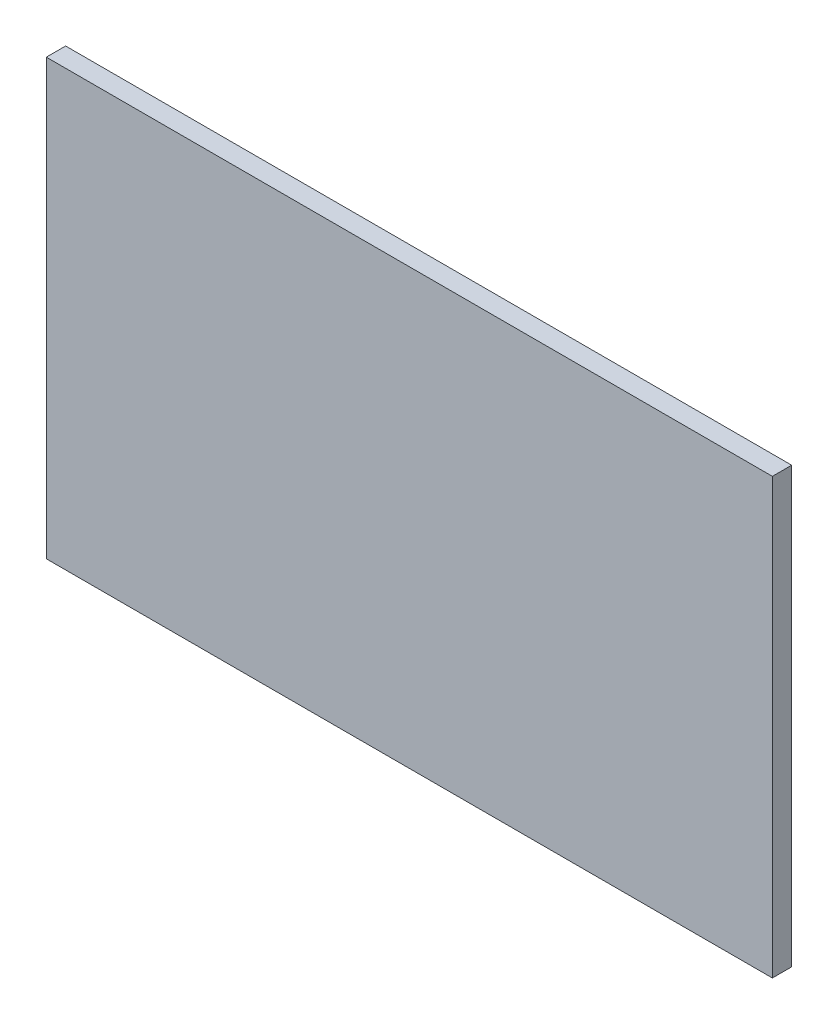
SolidWorks part; units mm, degrees
ref_plane "Спереди" through (0, 0, 0) normal (0, 0, 1) x (1, 0, 0)
ref_plane "Сверху" through (0, 0, 0) normal (0, 1, 0) x (1, 0, 0)
ref_plane "Справа" through (0, 0, 0) normal (1, 0, 0) x (0, 0, -1)
sketch "Эскиз1" plane through (0, 0, 0) normal (0, 0, 1) x (1, 0, 0)
  line L0 (0, 44.5194) -> (0, -185.4806) construction
  line L22 (-18, 39.5194) -> (-18, -185.4806) construction
  line L57 (188, 36.5194) -> (-188, 36.5194) construction
  line L85 (-53, 39.5194) -> (-53, -185.4806) construction
  line L122 (-188, -185.4806) -> (188, -185.4806)
  line L274 (-188, 39.5194) -> (-188, -185.4806)
  line L287 (-120.5, -2.6306) -> (-143, -2.6306)
  line L295 (-143, -2.6306) -> (-143, -11.8306)
  line L331 (188, -182.4806) -> (-188, -182.4806) construction
  line L332 (-185, -185.4806) -> (-185, 39.5194) construction
  line L345 (18, 39.5194) -> (18, -185.4806) construction
  line L348 (188, 39.5194) -> (188, -185.4806)
  line L349 (185, -185.4806) -> (185, 39.5194) construction
  line L361 (53, 39.5194) -> (53, -185.4806) construction
  line L619 (188, 39.5194) -> (-188, 39.5194)
  line L621 (-57.4, -29.0806) -> (-57.4, -17.8806)
  line L622 (-57.4, -17.8806) -> (-68.6, -17.8806)
  line L623 (-68.6, -29.0806) -> (-68.6, -17.8806)
  line L624 (-57.4, -29.0806) -> (-68.6, -29.0806)
  line L626 (-98, -2.6306) -> (-98, -11.8306)
  line L628 (-120.5, -11.8306) -> (-143, -11.8306)
  line L629 (-164.4, -29.0806) -> (-164.4, -17.8806)
  line L630 (-164.4, -17.8806) -> (-175.6, -17.8806)
  line L631 (-175.6, -29.0806) -> (-175.6, -17.8806)
  line L632 (-164.4, -29.0806) -> (-175.6, -29.0806)
  line L633 (-164.4, 0.9194) -> (-175.6, 0.9194)
  line L634 (-175.6, 0.9194) -> (-175.6, 12.1194)
  line L635 (-164.4, 12.1194) -> (-175.6, 12.1194)
  line L636 (-164.4, 0.9194) -> (-164.4, 12.1194)
  line L637 (-135.4, 0.9194) -> (-146.6, 0.9194)
  line L638 (-146.6, 0.9194) -> (-146.6, 12.1194)
  line L639 (-135.4, 12.1194) -> (-146.6, 12.1194)
  line L640 (-135.4, 0.9194) -> (-135.4, 12.1194)
  line L641 (-106.4, 0.9194) -> (-117.6, 0.9194)
  line L642 (-117.6, 0.9194) -> (-117.6, 12.1194)
  line L643 (-106.4, 12.1194) -> (-117.6, 12.1194)
  line L644 (-106.4, 0.9194) -> (-106.4, 12.1194)
  line L646 (-143, -2.6306) -> (-143, -11.8306)
  line L648 (-98, -11.8306) -> (-120.5, -11.8306)
  line L649 (-77.4, 0.9194) -> (-88.6, 0.9194)
  line L650 (-88.6, 0.9194) -> (-88.6, 12.1194)
  line L651 (-77.4, 12.1194) -> (-88.6, 12.1194)
  line L652 (-77.4, 0.9194) -> (-77.4, 12.1194)
  line L653 (-57.4, 0.9194) -> (-68.6, 0.9194)
  line L654 (-68.6, 0.9194) -> (-68.6, 12.1194)
  line L655 (-57.4, 12.1194) -> (-68.6, 12.1194)
  line L656 (-57.4, 0.9194) -> (-57.4, 12.1194)
  line L657 (-57.4, 18.9194) -> (-68.6, 18.9194)
  line L658 (-68.6, 18.9194) -> (-68.6, 30.1194)
  line L659 (-57.4, 30.1194) -> (-68.6, 30.1194)
  line L660 (-57.4, 18.9194) -> (-57.4, 30.1194)
  line L661 (-59.4, -96.8806) -> (-59.4, -110.0806)
  line L662 (-73.6, -110.0806) -> (-59.4, -110.0806)
  line L663 (-73.6, -96.8806) -> (-73.6, -110.0806)
  line L664 (-73.6, -96.8806) -> (-59.4, -96.8806)
  line L665 (-43.6, -121.0806) -> (-43.6, -109.8806)
  line L666 (-32.4, -109.8806) -> (-43.6, -109.8806)
  line L667 (-32.4, -121.0806) -> (-32.4, -109.8806)
  line L668 (-32.4, -121.0806) -> (-43.6, -121.0806)
  line L669 (-85.9, -115.8806) -> (-97.1, -115.8806)
  line L670 (-97.1, -127.0806) -> (-97.1, -115.8806)
  line L671 (-85.9, -127.0806) -> (-97.1, -127.0806)
  line L672 (-85.9, -127.0806) -> (-85.9, -115.8806)
  line L673 (-110.9, -115.8806) -> (-122.1, -115.8806)
  line L674 (-122.1, -127.0806) -> (-122.1, -115.8806)
  line L675 (-110.9, -127.0806) -> (-122.1, -127.0806)
  line L676 (-110.9, -127.0806) -> (-110.9, -115.8806)
  line L677 (-133.4, -131.3806) -> (-149.6, -131.3806)
  line L678 (-149.6, -147.5806) -> (-149.6, -131.3806)
  line L679 (-133.4, -147.5806) -> (-149.6, -147.5806)
  line L680 (-133.4, -147.5806) -> (-133.4, -131.3806)
  line L681 (-108.4, -131.3806) -> (-124.6, -131.3806)
  line L682 (-124.6, -147.5806) -> (-124.6, -131.3806)
  line L683 (-108.4, -147.5806) -> (-124.6, -147.5806)
  line L684 (-108.4, -147.5806) -> (-108.4, -131.3806)
  line L685 (-83.4, -131.3806) -> (-99.6, -131.3806)
  line L686 (-99.6, -147.5806) -> (-99.6, -131.3806)
  line L687 (-83.4, -147.5806) -> (-99.6, -147.5806)
  line L688 (-83.4, -147.5806) -> (-83.4, -131.3806)
  line L689 (-58.4, -131.3806) -> (-74.6, -131.3806)
  line L690 (-74.6, -147.5806) -> (-74.6, -131.3806)
  line L691 (-58.4, -147.5806) -> (-74.6, -147.5806)
  line L692 (-58.4, -147.5806) -> (-58.4, -131.3806)
  line L693 (-60.9, -151.8806) -> (-72.1, -151.8806)
  line L694 (-72.1, -163.0806) -> (-72.1, -151.8806)
  line L695 (-60.9, -163.0806) -> (-72.1, -163.0806)
  line L696 (-60.9, -163.0806) -> (-60.9, -151.8806)
  line L697 (-85.9, -151.8806) -> (-97.1, -151.8806)
  line L698 (-97.1, -163.0806) -> (-97.1, -151.8806)
  line L699 (-85.9, -163.0806) -> (-97.1, -163.0806)
  line L700 (-85.9, -163.0806) -> (-85.9, -151.8806)
  line L701 (-110.9, -151.8806) -> (-122.1, -151.8806)
  line L702 (-122.1, -163.0806) -> (-122.1, -151.8806)
  line L703 (-110.9, -163.0806) -> (-122.1, -163.0806)
  line L704 (-110.9, -163.0806) -> (-110.9, -151.8806)
  line L705 (-135.9, -151.8806) -> (-147.1, -151.8806)
  line L706 (-147.1, -163.0806) -> (-147.1, -151.8806)
  line L707 (-135.9, -163.0806) -> (-147.1, -163.0806)
  line L708 (-135.9, -163.0806) -> (-135.9, -151.8806)
  line L709 (-169.55, -161.5806) -> (-169.55, -135.3806)
  line L710 (-169.55, -135.3806) -> (-170.45, -135.3806)
  line L711 (-170.45, -161.5806) -> (-170.45, -135.3806)
  line L712 (-169.55, -161.5806) -> (-170.45, -161.5806)
  line L713 (-135.9, -181.0806) -> (-147.1, -181.0806)
  line L714 (-147.1, -181.0806) -> (-147.1, -169.8806)
  line L715 (-135.9, -169.8806) -> (-147.1, -169.8806)
  line L716 (-135.9, -181.0806) -> (-135.9, -169.8806)
  line L717 (-110.9, -181.0806) -> (-122.1, -181.0806)
  line L718 (-122.1, -181.0806) -> (-122.1, -169.8806)
  line L719 (-110.9, -169.8806) -> (-122.1, -169.8806)
  line L720 (-110.9, -181.0806) -> (-110.9, -169.8806)
  line L721 (-85.9, -181.0806) -> (-97.1, -181.0806)
  line L722 (-97.1, -181.0806) -> (-97.1, -169.8806)
  line L723 (-85.9, -169.8806) -> (-97.1, -169.8806)
  line L724 (-85.9, -181.0806) -> (-85.9, -169.8806)
  line L725 (-72.1, -181.0806) -> (-72.1, -169.8806)
  line L726 (-60.9, -169.8806) -> (-72.1, -169.8806)
  line L727 (-60.9, -181.0806) -> (-60.9, -169.8806)
  line L728 (-60.9, -181.0806) -> (-72.1, -181.0806)
  line L729 (-37.55, -158.5806) -> (-37.55, -132.3806)
  line L730 (-37.55, -132.3806) -> (-38.45, -132.3806)
  line L731 (-38.45, -158.5806) -> (-38.45, -132.3806)
  line L732 (-37.55, -158.5806) -> (-38.45, -158.5806)
  line L733 (-27.6, -157.7806) -> (-27.6, -133.1806)
  line L734 (-18.4, -133.1806) -> (-27.6, -133.1806)
  line L735 (-18.4, -157.7806) -> (-18.4, -133.1806)
  line L736 (-18.4, -157.7806) -> (-27.6, -157.7806)
  line L737 (13.1, -175.0306) -> (-13.1, -175.0306)
  line L738 (-13.1, -175.0306) -> (-13.1, -175.9306)
  line L739 (13.1, -175.9306) -> (-13.1, -175.9306)
  line L740 (13.1, -175.0306) -> (13.1, -175.9306)
  line L741 (5.6, -121.0806) -> (-5.6, -121.0806)
  line L742 (-5.6, -121.0806) -> (-5.6, -109.8806)
  line L743 (5.6, -109.8806) -> (-5.6, -109.8806)
  line L744 (5.6, -121.0806) -> (5.6, -109.8806)
  line L745 (32.4, -121.0806) -> (43.6, -121.0806)
  line L746 (43.6, -121.0806) -> (43.6, -109.8806)
  line L747 (32.4, -109.8806) -> (43.6, -109.8806)
  line L748 (32.4, -121.0806) -> (32.4, -109.8806)
  line L749 (73.6, -110.0806) -> (59.4, -110.0806)
  line L750 (59.4, -96.8806) -> (59.4, -110.0806)
  line L751 (73.6, -96.8806) -> (59.4, -96.8806)
  line L752 (73.6, -96.8806) -> (73.6, -110.0806)
  line L753 (85.9, -127.0806) -> (85.9, -115.8806)
  line L754 (85.9, -115.8806) -> (97.1, -115.8806)
  line L755 (97.1, -127.0806) -> (97.1, -115.8806)
  line L756 (85.9, -127.0806) -> (97.1, -127.0806)
  line L757 (58.4, -131.3806) -> (74.6, -131.3806)
  line L758 (74.6, -147.5806) -> (74.6, -131.3806)
  line L759 (58.4, -147.5806) -> (74.6, -147.5806)
  line L760 (58.4, -147.5806) -> (58.4, -131.3806)
  line L761 (83.4, -131.3806) -> (99.6, -131.3806)
  line L762 (99.6, -147.5806) -> (99.6, -131.3806)
  line L763 (83.4, -147.5806) -> (99.6, -147.5806)
  line L764 (83.4, -147.5806) -> (83.4, -131.3806)
  line L765 (110.9, -127.0806) -> (110.9, -115.8806)
  line L766 (110.9, -115.8806) -> (122.1, -115.8806)
  line L767 (122.1, -127.0806) -> (122.1, -115.8806)
  line L768 (110.9, -127.0806) -> (122.1, -127.0806)
  line L769 (38.45, -158.5806) -> (38.45, -132.3806)
  line L770 (37.55, -132.3806) -> (38.45, -132.3806)
  line L771 (37.55, -158.5806) -> (37.55, -132.3806)
  line L772 (37.55, -158.5806) -> (38.45, -158.5806)
  line L773 (18.4, -133.1806) -> (27.6, -133.1806)
  line L774 (27.6, -157.7806) -> (27.6, -133.1806)
  line L775 (18.4, -157.7806) -> (27.6, -157.7806)
  line L776 (18.4, -157.7806) -> (18.4, -133.1806)
  line L777 (60.9, -181.0806) -> (60.9, -169.8806)
  line L778 (60.9, -169.8806) -> (72.1, -169.8806)
  line L779 (72.1, -181.0806) -> (72.1, -169.8806)
  line L780 (60.9, -181.0806) -> (72.1, -181.0806)
  line L781 (60.9, -163.0806) -> (60.9, -151.8806)
  line L782 (60.9, -151.8806) -> (72.1, -151.8806)
  line L783 (72.1, -163.0806) -> (72.1, -151.8806)
  line L784 (60.9, -163.0806) -> (72.1, -163.0806)
  line L785 (85.9, -163.0806) -> (85.9, -151.8806)
  line L786 (85.9, -151.8806) -> (97.1, -151.8806)
  line L787 (97.1, -163.0806) -> (97.1, -151.8806)
  line L788 (85.9, -163.0806) -> (97.1, -163.0806)
  line L789 (85.9, -181.0806) -> (85.9, -169.8806)
  line L790 (85.9, -169.8806) -> (97.1, -169.8806)
  line L791 (97.1, -181.0806) -> (97.1, -169.8806)
  line L792 (85.9, -181.0806) -> (97.1, -181.0806)
  line L793 (110.9, -181.0806) -> (110.9, -169.8806)
  line L794 (110.9, -169.8806) -> (122.1, -169.8806)
  line L795 (122.1, -181.0806) -> (122.1, -169.8806)
  line L796 (110.9, -181.0806) -> (122.1, -181.0806)
  line L797 (110.9, -163.0806) -> (110.9, -151.8806)
  line L798 (110.9, -151.8806) -> (122.1, -151.8806)
  line L799 (122.1, -163.0806) -> (122.1, -151.8806)
  line L800 (110.9, -163.0806) -> (122.1, -163.0806)
  line L801 (108.4, -147.5806) -> (108.4, -131.3806)
  line L802 (108.4, -131.3806) -> (124.6, -131.3806)
  line L803 (124.6, -147.5806) -> (124.6, -131.3806)
  line L804 (108.4, -147.5806) -> (124.6, -147.5806)
  line L805 (133.4, -147.5806) -> (133.4, -131.3806)
  line L806 (133.4, -131.3806) -> (149.6, -131.3806)
  line L807 (149.6, -147.5806) -> (149.6, -131.3806)
  line L808 (133.4, -147.5806) -> (149.6, -147.5806)
  line L809 (135.9, -163.0806) -> (135.9, -151.8806)
  line L810 (135.9, -151.8806) -> (147.1, -151.8806)
  line L811 (147.1, -163.0806) -> (147.1, -151.8806)
  line L812 (135.9, -163.0806) -> (147.1, -163.0806)
  line L813 (135.9, -181.0806) -> (135.9, -169.8806)
  line L814 (135.9, -169.8806) -> (147.1, -169.8806)
  line L815 (147.1, -181.0806) -> (147.1, -169.8806)
  line L816 (135.9, -181.0806) -> (147.1, -181.0806)
  line L817 (170.45, -161.5806) -> (170.45, -135.3806)
  line L818 (169.55, -135.3806) -> (170.45, -135.3806)
  line L819 (169.55, -161.5806) -> (169.55, -135.3806)
  line L820 (169.55, -161.5806) -> (170.45, -161.5806)
  line L821 (57.4, -17.8806) -> (68.6, -17.8806)
  line L822 (68.6, -29.0806) -> (68.6, -17.8806)
  line L823 (57.4, -29.0806) -> (68.6, -29.0806)
  line L824 (57.4, -29.0806) -> (57.4, -17.8806)
  line L825 (57.4, 0.9194) -> (68.6, 0.9194)
  line L826 (68.6, 0.9194) -> (68.6, 12.1194)
  line L827 (57.4, 12.1194) -> (68.6, 12.1194)
  line L828 (57.4, 0.9194) -> (57.4, 12.1194)
  line L829 (88.6, 0.9194) -> (77.4, 0.9194)
  line L830 (77.4, 0.9194) -> (77.4, 12.1194)
  line L831 (88.6, 12.1194) -> (77.4, 12.1194)
  line L832 (88.6, 0.9194) -> (88.6, 12.1194)
  line L833 (117.6, 0.9194) -> (106.4, 0.9194)
  line L834 (106.4, 0.9194) -> (106.4, 12.1194)
  line L835 (117.6, 12.1194) -> (106.4, 12.1194)
  line L836 (117.6, 0.9194) -> (117.6, 12.1194)
  line L837 (146.6, 0.9194) -> (135.4, 0.9194)
  line L838 (135.4, 0.9194) -> (135.4, 12.1194)
  line L839 (146.6, 12.1194) -> (135.4, 12.1194)
  line L840 (146.6, 0.9194) -> (146.6, 12.1194)
  line L841 (175.6, 0.9194) -> (164.4, 0.9194)
  line L842 (164.4, 0.9194) -> (164.4, 12.1194)
  line L843 (175.6, 12.1194) -> (164.4, 12.1194)
  line L844 (175.6, 0.9194) -> (175.6, 12.1194)
  line L845 (164.4, -17.8806) -> (175.6, -17.8806)
  line L846 (175.6, -29.0806) -> (175.6, -17.8806)
  line L847 (164.4, -29.0806) -> (175.6, -29.0806)
  line L848 (164.4, -29.0806) -> (164.4, -17.8806)
  line L849 (68.6, 18.9194) -> (68.6, 30.1194)
  line L850 (57.4, 30.1194) -> (68.6, 30.1194)
  line L851 (57.4, 18.9194) -> (57.4, 30.1194)
  line L852 (57.4, 18.9194) -> (68.6, 18.9194)
  line L853 (3.4, -74.8806) -> (14.6, -74.8806)
  line L854 (14.6, -86.0806) -> (14.6, -74.8806)
  line L855 (3.4, -86.0806) -> (14.6, -86.0806)
  line L856 (3.4, -86.0806) -> (3.4, -74.8806)
  line L857 (-3.4, -74.8806) -> (-14.6, -74.8806)
  line L858 (-14.6, -86.0806) -> (-14.6, -74.8806)
  line L859 (-3.4, -86.0806) -> (-14.6, -86.0806)
  line L860 (-3.4, -86.0806) -> (-3.4, -74.8806)
  line L861 (-3.4, -66.0806) -> (-14.6, -66.0806)
  line L862 (-14.6, -66.0806) -> (-14.6, -54.8806)
  line L863 (-3.4, -54.8806) -> (-14.6, -54.8806)
  line L864 (-3.4, -66.0806) -> (-3.4, -54.8806)
  line L865 (3.4, -66.0806) -> (14.6, -66.0806)
  line L866 (14.6, -66.0806) -> (14.6, -54.8806)
  line L867 (3.4, -54.8806) -> (14.6, -54.8806)
  line L868 (3.4, -66.0806) -> (3.4, -54.8806)
  line L869 (98, -11.8306) -> (120.5, -11.8306)
  line L870 (98, -2.6306) -> (98, -11.8306)
  line L871 (98, -2.6306) -> (120.5, -2.6306)
  line L872 (120.5, -2.6306) -> (143, -2.6306)
  line L873 (143, -2.6306) -> (143, -11.8306)
  line L874 (120.5, -11.8306) -> (143, -11.8306)
  line L879 (-98, -2.6306) -> (-98, -11.8306)
  line L880 (-98, -2.6306) -> (-120.5, -2.6306)
  circle A0 centre (-38, -95.4806) radius 2.9
  circle A22 centre (-120.5, -62.4806) radius 17
  circle A56 centre (120.5, -62.4806) radius 17
  circle A60 centre (-83, 24.5194) radius 2.9
  circle A61 centre (-112, 24.5194) radius 2.9
  circle A62 centre (-141, 24.5194) radius 2.9
  circle A63 centre (-170, 24.5194) radius 2.9
  circle A64 centre (-38, 24.5194) radius 2.9
  circle A65 centre (-38, -5.4806) radius 2.9
  circle A66 centre (-38, -35.4806) radius 2.9
  circle A67 centre (-24, -10.4806) radius 2.5
  circle A68 centre (-24, -40.4806) radius 2.5
  circle A69 centre (-38, -65.4806) radius 2.9
  circle A71 centre (-66.5, -121.4806) radius 3.1
  circle A72 centre (-141.5, -121.4806) radius 3.1
  circle A73 centre (-170, -121.4806) radius 2.5
  circle A74 centre (-170, -175.4806) radius 2.5
  circle A75 centre (83, 24.5194) radius 2.9
  circle A76 centre (112, 24.5194) radius 2.9
  circle A77 centre (141, 24.5194) radius 2.9
  circle A78 centre (170, 24.5194) radius 2.9
  circle A79 centre (0, 24.5194) radius 2.9
  circle A80 centre (0, -5.4806) radius 3.1
  circle A81 centre (0, -35.4806) radius 2.9
  circle A82 centre (-24, -70.4806) radius 2.5
  circle A83 centre (38, 24.5194) radius 2.9
  circle A84 centre (38, -5.4806) radius 2.9
  circle A85 centre (38, -35.4806) radius 2.9
  circle A86 centre (38, -65.4806) radius 2.9
  circle A87 centre (24, -10.4806) radius 2.5
  circle A88 centre (24, -40.4806) radius 2.5
  circle A89 centre (24, -70.4806) radius 2.5
  circle A90 centre (38, -95.4806) radius 2.9
  circle A91 centre (66.5, -121.4806) radius 3.1
  circle A92 centre (141.5, -121.4806) radius 3.1
  circle A93 centre (170, -121.4806) radius 2.5
  circle A94 centre (170, -175.4806) radius 2.5
  point P3 (0, -5.4806)
  point P29 (-38, -145.4806)
  point P34 (-38, -145.4806)
  point P44 (-38, -115.4806)
  point P86 (0, -115.4806)
  point P87 (-24, -10.4806)
  point P94 (-24, -40.4806)
  point P116 (0, -175.4806)
  point P121 (0, -175.4806)
  point P167 (-170, 6.5194)
  point P172 (-141, 6.5194)
  point P177 (-112, 6.5194)
  point P187 (-63, 24.5194)
  point P192 (-116.5, -121.4806)
  point P197 (-91.5, -121.4806)
  point P202 (-141.5, -157.4806)
  point P217 (-66.5, -157.4806)
  point P227 (-116.5, -175.4806)
  point P270 (-104, -139.4806)
  point P272 (-170, -148.4806)
  point P277 (-170, -148.4806)
  point P282 (-170, -175.4806)
  point P289 (-170, -121.4806)
  point P298 (-66.5, -121.4806)
  point P305 (-141.5, -121.4806)
  point P337 (-24, -70.4806)
  point P349 (-63, -23.4806)
  point P364 (-66.5, -103.4806)
  point P446 (38, -145.4806)
  point P625 (104, -139.4806)
  point P644 (0, -182.4806)
  dimension "D7" = 3
  dimension "D10" = 376
  dimension "D55" = 3
  dimension "D56" = 3
  dimension "D58" = 225
sketch "Эскиз2" plane through (0, 0, 0) normal (0, 0, 1) x (1, 0, 0)
  line L1 (-188, 39.5194) -> (188, 39.5194)
  line L2 (-188, 39.5194) -> (-188, -185.4806)
  line L3 (-188, -185.4806) -> (188, -185.4806)
  line L4 (188, 39.5194) -> (188, -185.4806)
extrude "Бобышка-Вытянуть1" add sketch "Эскиз2" against normal blind 10
